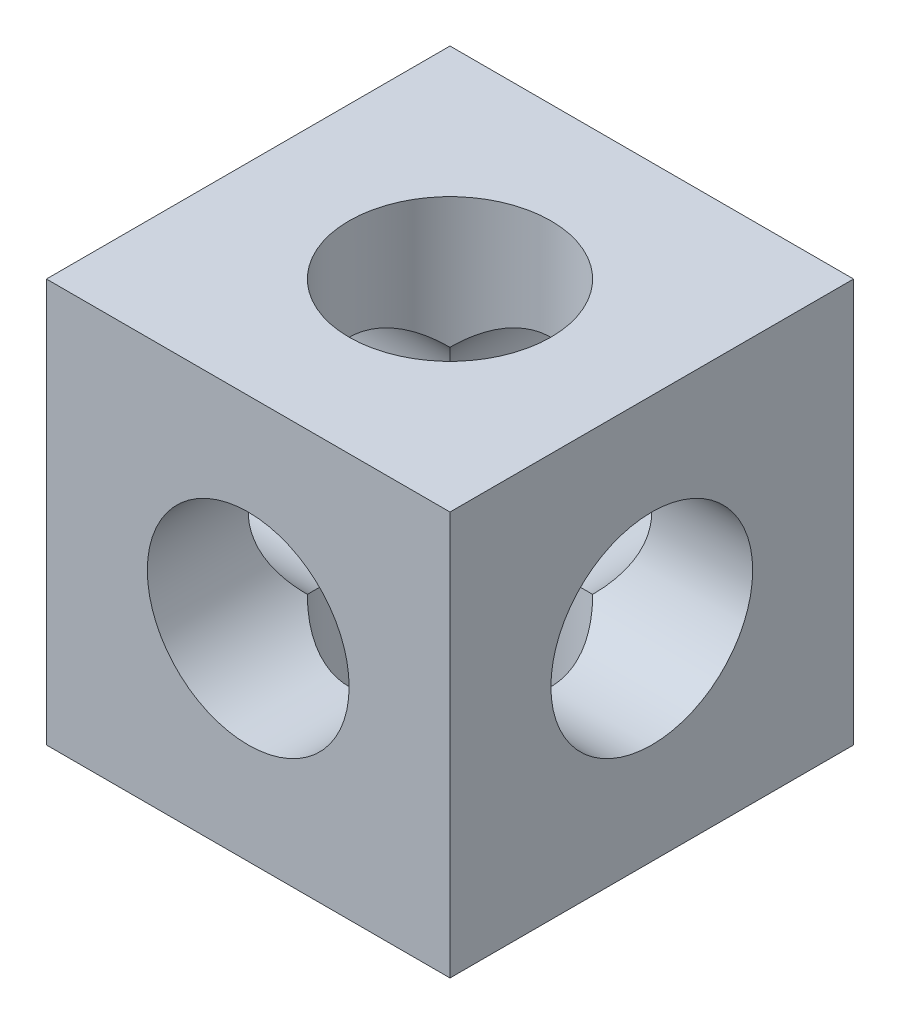
SolidWorks part; units mm, degrees
ref_plane "前视基准面" through (0, 0, 0) normal (0, 0, 1) x (1, 0, 0)
ref_plane "上视基准面" through (0, 0, 0) normal (0, 1, 0) x (1, 0, 0)
ref_plane "右视基准面" through (0, 0, 0) normal (1, 0, 0) x (0, 0, -1)
other "Configuration Table"
sketch "草图1" plane through (0, 0, 0) normal (0, 0, 1) x (1, 0, 0)
  line L1 (-3, 3) -> (3, 3)
  line L2 (-3, 3) -> (-3, -3)
  line L3 (-3, -3) -> (3, -3)
  line L4 (3, 3) -> (3, -3)
  line L5 (-3, 3) -> (3, -3) construction
  line L6 (-3, -3) -> (3, 3) construction
  point P0 (0, 0)
  dimension "D1" = 6
  dimension "D2" = 6
extrude "凸台-拉伸1" add sketch "草图1" along normal blind 6
sketch "草图2" plane through (0, 0, 6) normal (0, 0, 1) x (1, 0, 0)
  circle A0 centre (0, 0) radius 1.5
  dimension "D1" = 3
extrude "切除-拉伸1" cut sketch "草图2" against normal through all
sketch "草图3" plane through (3, 0, 0) normal (1, 0, 0) x (0, 0, -1)
  line L0 (-3, 3) -> (-3, -5.568) construction
  line L1 (-6, 3) -> (0, 3) construction
  circle A0 centre (-3, 0) radius 1.5
  dimension "D1" = 3
extrude "切除-拉伸2" cut sketch "草图3" against normal through all
sketch "草图4" plane through (0, 3, 0) normal (0, 1, 0) x (1, 0, 0)
  line L0 (3, -3) -> (-8.5775, -3) construction
  line L1 (3, -6) -> (3, 0) construction
  circle A0 centre (0, -3) radius 1.5
  dimension "D1" = 3
extrude "切除-拉伸3" cut sketch "草图4" against normal through all
